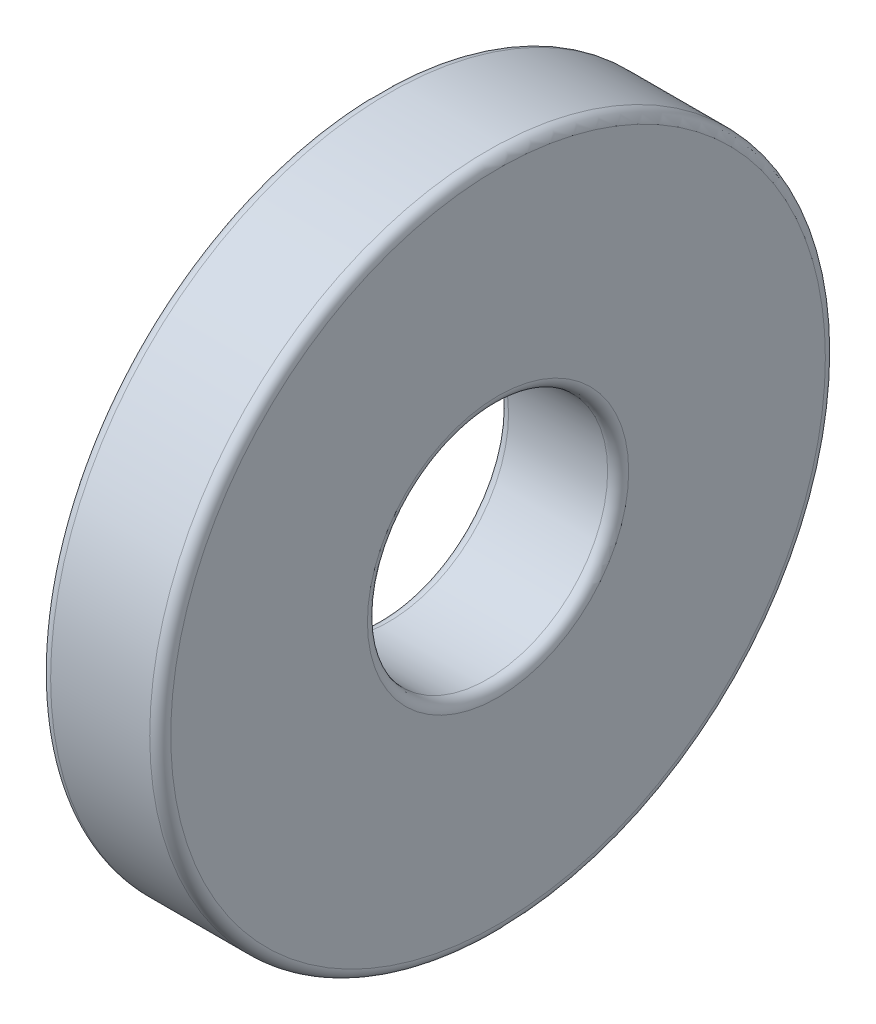
SolidWorks part; units mm, degrees
ref_plane "Front Plane" through (0, 0, 0) normal (0, 0, 1) x (1, 0, 0)
ref_plane "Top Plane" through (0, 0, 0) normal (0, 1, 0) x (1, 0, 0)
ref_plane "Right Plane" through (0, 0, 0) normal (1, 0, 0) x (0, 0, -1)
sketch "Sketch1" plane through (0, 0, 0) normal (1, 0, 0) x (0, 0, -1)
  circle A0 centre (0, 0) radius 11.25
  circle A1 centre (0, 0) radius 4
  dimension "D1" = 22.5
  dimension "D2" = 8
extrude "Boss-Extrude1" add sketch "Sketch1" along normal blind 4
fillet "Fillet2" radius 0.35 4 edges at (0, 0, -4) (0, 0, -11.25) (4, 0, -4) (4, 0, -11.25)
